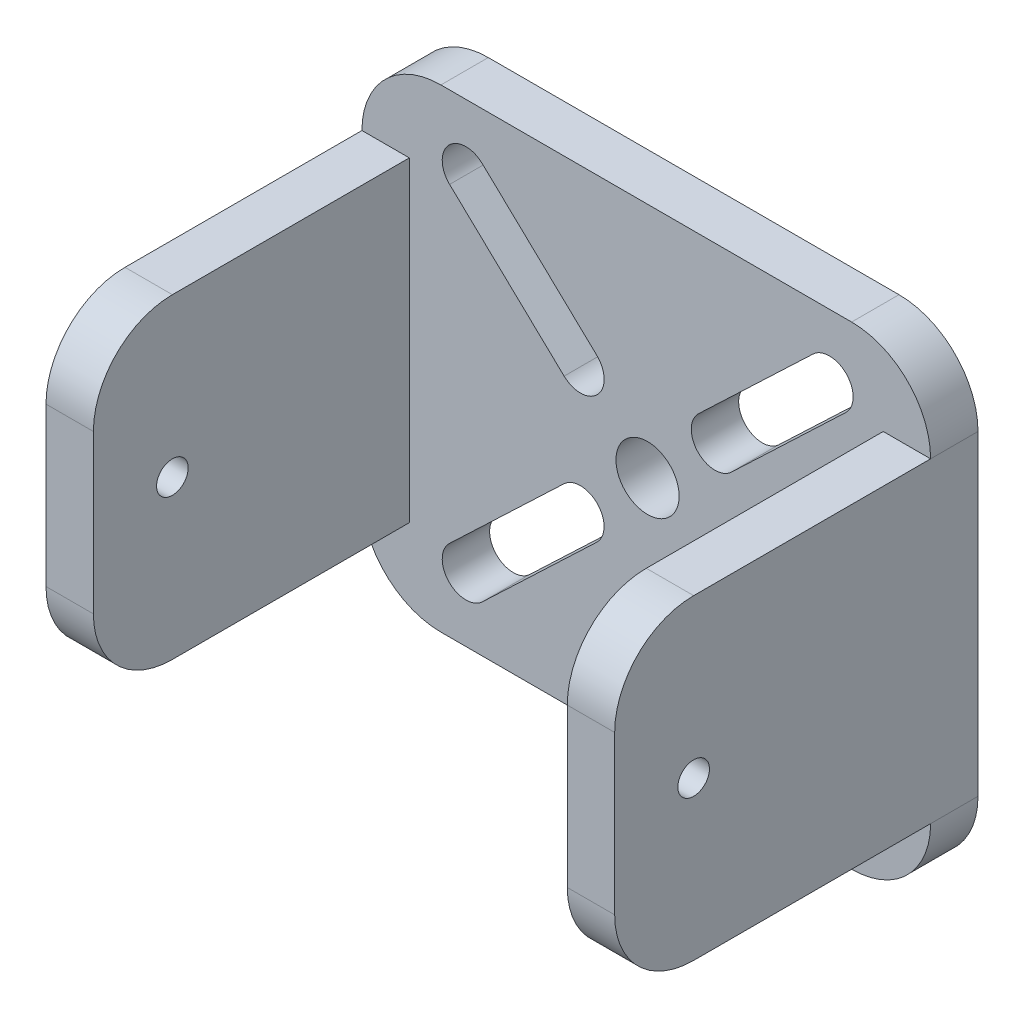
SolidWorks part; units mm, degrees
ref_plane "Front Plane" through (0, 0, 0) normal (0, 0, 1) x (1, 0, 0)
ref_plane "Top Plane" through (0, 0, 0) normal (0, 1, 0) x (1, 0, 0)
ref_plane "Right Plane" through (0, 0, 0) normal (1, 0, 0) x (0, 0, -1)
sketch "Sketch1" plane through (0, 0, 0) normal (0, 0, 1) x (1, 0, 0)
  line L0 (2.297, 29.9783) -> (33.8639, 0)
  line L1 (0, 0) -> (36, 0)
  line L2 (0, 0) -> (0, 30)
  line L3 (0, 30) -> (36, 30)
  line L4 (36, 0) -> (36, 30)
  line L5 (2.297, -0.0217) -> (33.8639, 30)
  line L6 (33.8639, 30) -> (18.0804, 14.9891)
  line L7 (33.8639, 30) -> (18.0804, 14.9891)
  line L8 (29.5952, 25.9403) -> (22.349, 19.0488) construction
  line L9 (30.629, 24.8534) -> (23.3828, 17.9619)
  line L10 (28.5615, 27.0272) -> (21.3153, 20.1357)
  line L11 (22.349, 10.9353) -> (29.6002, 4.0491) construction
  line L12 (23.382, 12.023) -> (30.6332, 5.1367)
  line L13 (21.3161, 9.8477) -> (28.5673, 2.9614)
  line L14 (13.8285, 10.9453) -> (6.5823, 4.0538) construction
  line L15 (14.8622, 9.8584) -> (7.616, 2.9669)
  line L16 (12.7947, 12.0322) -> (5.5486, 5.1407)
  line L17 (6.5823, 25.9087) -> (13.8335, 19.0224) construction
  line L18 (7.6152, 26.9963) -> (14.8664, 20.1101)
  line L19 (5.5493, 24.821) -> (12.8005, 17.9347)
  circle A0 centre (18.0804, 14.9891) radius 2
  arc A1 (30.629, 24.8534) -> (28.5615, 27.0272) centre (29.5952, 25.9403) ccw
  arc A2 (21.3153, 20.1357) -> (23.3828, 17.9619) centre (22.349, 19.0488) ccw
  arc A3 (23.382, 12.023) -> (21.3161, 9.8477) centre (22.349, 10.9353) ccw
  arc A4 (28.5673, 2.9614) -> (30.6332, 5.1367) centre (29.6002, 4.0491) ccw
  arc A5 (14.8622, 9.8584) -> (12.7947, 12.0322) centre (13.8285, 10.9453) ccw
  arc A6 (5.5486, 5.1407) -> (7.616, 2.9669) centre (6.5823, 4.0538) ccw
  arc A7 (7.6152, 26.9963) -> (5.5493, 24.821) centre (6.5823, 25.9087) ccw
  arc A8 (12.8005, 17.9347) -> (14.8664, 20.1101) centre (13.8335, 19.0224) ccw
  point P10 (18.0804, 14.9891)
  point P13 (18.0804, 14.9891)
  point P15 (25.9721, 22.4946)
  point P22 (25.9746, 7.4922)
  point P29 (10.2054, 7.4996)
  point P36 (10.2079, 22.4655)
  dimension "D1" = 30
  dimension "D2" = 36
extrude "Boss-Extrude2" add sketch "Sketch1" along normal blind 3
sketch "Sketch2" plane through (36, 0, 0) normal (1, 0, 0) x (0, 0, -1)
  line L0 (-3, 0) -> (-3, 30) construction
  line L1 (-18, 5) -> (-3, 5)
  line L2 (-23, 10) -> (-23, 20)
  line L3 (-18, 25) -> (-3, 25)
  line L4 (-3, 5) -> (-3, 25)
  line L5 (-23, 5) -> (-3, 25) construction
  line L6 (-23, 25) -> (-3, 5) construction
  circle A0 centre (-18, 15) radius 1
  arc A1 (-18, 5) -> (-23, 10) centre (-18, 10) cw
  arc A2 (-23, 20) -> (-18, 25) centre (-18, 20) cw
  point P0 (-13, 15)
  dimension "D4" = 2
  dimension "D6" = 5
  dimension "D1" = 20
  dimension "D2" = 5
  dimension "D3" = 20
  dimension "D5" = 15
extrude "Boss-Extrude3" add sketch "Sketch2" against normal blind 3
sketch "Sketch3" plane through (0, 0, 0) normal (-1, 0, 0) x (0, 0, 1)
  line L0 (3, 25) -> (18, 25)
  line L1 (23, 20) -> (23, 10)
  line L2 (18, 5) -> (3, 5)
  line L3 (3, 5) -> (3, 25)
  arc A0 (18, 25) -> (23, 20) centre (18, 20) cw
  arc A1 (23, 10) -> (18, 5) centre (18, 10) cw
  circle A2 centre (18, 15) radius 1
extrude "Boss-Extrude4" add sketch "Sketch3" against normal blind 3
fillet "Fillet1" radius 5 4 edges at (36, 30, 1.5) (0, 30, 1.5) (0, 0, 1.5) (36, 0, 1.5)
